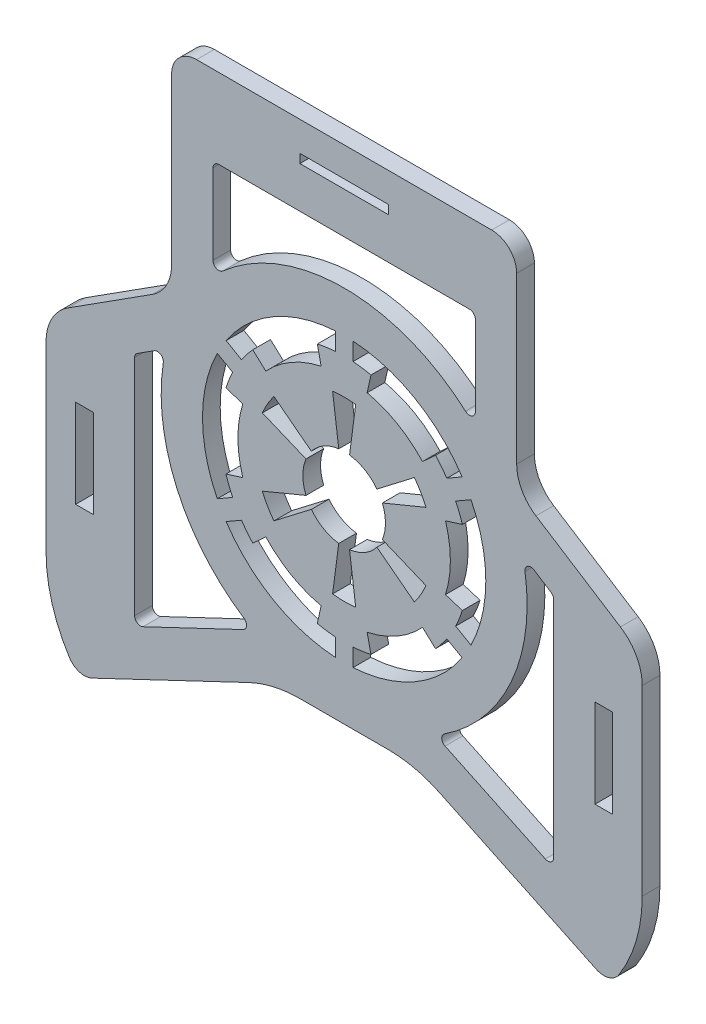
SolidWorks part; units mm, degrees
ref_plane "Front Plane" through (0, 0, 0) normal (0, 0, 1) x (1, 0, 0)
ref_plane "Top Plane" through (0, 0, 0) normal (0, 1, 0) x (1, 0, 0)
ref_plane "Right Plane" through (0, 0, 0) normal (1, 0, 0) x (0, 0, -1)
sketch "Sketch2" plane through (0, 0, 0) normal (0, 0, 1) x (1, 0, 0)
  line L4 (93, 2.1) -> (93, 62.1)
  line L5 (68, 87.1) -> (17, 87.1)
  line L6 (-8, 62.1) -> (-8, 2.1)
  line L7 (17, -22.9) -> (68, -22.9)
  line L8 (93, 2.1) -> (93, 62.1)
  line L9 (68, 87.1) -> (17, 87.1)
  line L10 (-8, 62.1) -> (-8, 2.1)
  line L11 (17, -22.9) -> (68, -22.9)
  line L13 (-3, 26.6) -> (-3, 11.6)
  line L14 (0, 26.6) -> (-3, 26.6)
  line L15 (0, 11.6) -> (0, 26.6)
  line L16 (-3, 11.6) -> (0, 11.6)
  line L17 (-3, 26.6) -> (-3, 11.6)
  line L18 (0, 26.6) -> (-3, 26.6)
  line L19 (0, 11.6) -> (0, 26.6)
  line L20 (-3, 11.6) -> (0, 11.6)
  line L22 (85, 26.6) -> (85, 11.6)
  line L23 (88, 26.6) -> (85, 26.6)
  line L24 (88, 11.6) -> (88, 26.6)
  line L25 (85, 11.6) -> (88, 11.6)
  line L26 (85, 26.6) -> (85, 11.6)
  line L27 (88, 26.6) -> (85, 26.6)
  line L28 (88, 11.6) -> (88, 26.6)
  line L29 (85, 11.6) -> (88, 11.6)
  line L31 (35, 82.1) -> (35, 80.6)
  line L32 (50, 82.1) -> (35, 82.1)
  line L33 (50, 80.6) -> (50, 82.1)
  line L34 (35, 80.6) -> (50, 80.6)
  line L35 (35, 82.1) -> (35, 80.6)
  line L36 (50, 82.1) -> (35, 82.1)
  line L37 (50, 80.6) -> (50, 82.1)
  line L38 (35, 80.6) -> (50, 80.6)
  arc A4 (93, 62.1) -> (68, 87.1) centre (68, 62.1) ccw
  arc A5 (17, 87.1) -> (-8, 62.1) centre (17, 62.1) ccw
  arc A6 (-8, 2.1) -> (17, -22.9) centre (17, 2.1) ccw
  arc A7 (68, -22.9) -> (93, 2.1) centre (68, 2.1) ccw
  arc A8 (93, 62.1) -> (68, 87.1) centre (68, 62.1) ccw
  arc A9 (17, 87.1) -> (-8, 62.1) centre (17, 62.1) ccw
  arc A10 (-8, 2.1) -> (17, -22.9) centre (17, 2.1) ccw
  arc A11 (68, -22.9) -> (93, 2.1) centre (68, 2.1) ccw
  dimension "D1" = 0
  dimension "D2" = 0
  dimension "D3" = 0
  dimension "D4" = 0
extrude "Boss-Extrude1" add sketch "Sketch2" along normal blind 3
sketch "Sketch3" plane through (0, 0, 3) normal (0, 0, 1) x (1, 0, 0)
  line L0 (68, 87.1) -> (17, 87.1) construction
  line L1 (13.2678, 82.8678) -> (13.2678, 54.8678)
  line L2 (10, 48.9032) -> (-8, 37.4065)
  line L3 (-8, 62.1) -> (-8, 2.1) construction
  line L4 (-2.4738, -13.577) -> (30.5, 2.1)
  line L5 (30.5, 2.1) -> (54.5, 2.1)
  line L6 (42.5, 87.1) -> (42.5, -22.9) construction
  line L7 (17, -22.9) -> (68, -22.9) construction
  line L8 (17.5, 87.1) -> (67.5, 87.1)
  line L9 (-8, 37.4065) -> (-8, 106.023)
  line L10 (-8, 106.023) -> (93, 106.023)
  line L11 (-2.4738, -13.577) -> (-2.4738, -35.5328)
  line L12 (-2.4738, -35.5328) -> (87.4738, -35.5328)
  line L13 (87.4738, -13.577) -> (87.4738, -35.5328)
  line L14 (93, 37.4065) -> (93, 106.023)
  line L15 (87.4738, -13.577) -> (54.5, 2.1)
  line L16 (75, 48.9032) -> (93, 37.4065)
  line L17 (71.7322, 82.8678) -> (71.7322, 54.8678)
  arc A0 (17.5, 87.1) -> (13.2678, 82.8678) centre (17.5, 82.8678) ccw
  arc A1 (13.2678, 54.8678) -> (10, 48.9032) centre (6.1904, 54.8678) cw
  arc A2 (-8, 2.1) -> (17, -22.9) centre (17, 2.1) ccw construction
  arc A3 (71.7322, 54.8678) -> (75, 48.9032) centre (78.8096, 54.8678) ccw
  arc A4 (67.5, 87.1) -> (71.7322, 82.8678) centre (67.5, 82.8678) cw
  point P29 (42.5, 2.1)
  point P30 (42.5, 106.023)
  point P31 (42.5, -35.5328)
  dimension "D1" = 12
  dimension "D2" = 25
  dimension "D3" = 25
  dimension "D4" = 28
  dimension "D6" = 18
extrude "Cut-Extrude1" cut sketch "Sketch3" against normal through all
fillet "Fillet1" radius 3 2 edges at (-2.4738, -13.577, 1.5) (87.4738, -13.577, 1.5)
fillet "Fillet2" radius 20 2 edges at (30.5, 2.1, 1.5) (54.5, 2.1, 1.5)
fillet "Fillet3" radius 8 2 edges at (-8, 37.4065, 1.5) (93, 37.4065, 1.5)
sketch "Sketch5" plane through (0, 0, 3) normal (0, 0, 1) x (1, 0, 0)
  line L0 (42.5, 87.1) -> (42.5, 2.1) construction
  line L1 (67.5, 87.1) -> (17.5, 87.1) construction
  line L2 (49.9876, 2.1) -> (35.0124, 2.1) construction
  line L3 (149.0087, 53.9587) -> (120.8587, 53.9587) construction
  line L4 (146.9102, 53.2087) -> (145.4069, 53.2087)
  line L5 (146.9102, 54.7087) -> (145.4069, 54.7087)
  line L6 (146.9102, 54.7087) -> (146.1585, 53.9587) construction
  line L7 (146.1585, 53.9587) -> (145.4069, 53.2087) construction
  line L8 (134.9337, 53.9587) -> (145.1848, 56.2313) construction
  line L9 (134.9337, 53.9587) -> (145.1848, 51.6861) construction
  line L10 (145.1848, 51.6861) -> (145.1848, 53.9587) construction
  line L11 (145.1848, 53.9587) -> (145.1848, 56.2313) construction
  line L12 (145.1848, 56.2313) -> (143.7203, 55.9066)
  line L13 (145.1848, 51.6861) -> (143.7203, 52.0107)
  line L14 (140.2724, 43.2117) -> (139.5208, 44.5137)
  line L15 (138.0911, 43.9447) -> (137.64, 45.3752)
  line L16 (142.0274, 46.2173) -> (141.014, 47.3232)
  line L17 (141.5715, 43.9617) -> (140.8198, 45.2637)
  line L18 (128.2959, 43.9617) -> (129.0476, 45.2637)
  line L19 (127.84, 46.2173) -> (128.8534, 47.3232)
  line L20 (131.7763, 43.9447) -> (132.2273, 45.3752)
  line L21 (129.5949, 43.2117) -> (130.3466, 44.5137)
  line L22 (122.9571, 54.7087) -> (124.4605, 54.7087)
  line L23 (124.6826, 56.2313) -> (126.147, 55.9066)
  line L24 (124.6826, 51.6861) -> (126.147, 52.0107)
  line L25 (122.9571, 53.2087) -> (124.4605, 53.2087)
  line L26 (129.5949, 64.7057) -> (130.3466, 63.4037)
  line L27 (131.7763, 63.9727) -> (132.2273, 62.5421)
  line L28 (127.84, 61.7001) -> (128.8534, 60.5942)
  line L29 (128.2959, 63.9557) -> (129.0476, 62.6537)
  line L30 (141.5715, 63.9557) -> (140.8198, 62.6537)
  line L31 (142.0274, 61.7001) -> (141.014, 60.5942)
  line L32 (138.0911, 63.9727) -> (137.64, 62.5421)
  line L33 (140.2724, 64.7057) -> (139.5208, 63.4037)
  line L34 (134.9337, 53.9587) -> (142.3695, 54.9376) construction
  line L35 (134.9337, 53.9587) -> (142.3695, 52.9797) construction
  line L36 (142.3695, 52.9797) -> (142.3695, 53.9587) construction
  line L37 (142.3695, 53.9587) -> (142.3695, 54.9376) construction
  line L38 (142.3695, 54.9376) -> (138.4037, 54.4155)
  line L39 (142.3695, 52.9797) -> (138.4037, 53.5019)
  line L40 (139.4994, 48.0085) -> (137.0643, 51.182)
  line L41 (137.8038, 47.0296) -> (136.2731, 50.7251)
  line L42 (132.0636, 47.0296) -> (133.5943, 50.7251)
  line L43 (130.368, 48.0085) -> (132.803, 51.182)
  line L44 (127.4978, 52.9797) -> (131.4636, 53.5019)
  line L45 (127.4978, 54.9376) -> (131.4636, 54.4155)
  line L46 (130.368, 59.9088) -> (132.803, 56.7354)
  line L47 (132.0636, 60.8878) -> (133.5943, 57.1923)
  line L48 (137.8038, 60.8878) -> (136.2731, 57.1923)
  line L49 (139.4994, 59.9088) -> (137.0643, 56.7354)
  line L50 (41, 59.0531) -> (41, 56.0464)
  line L51 (41, 56.0464) -> (42.5, 57.5497) construction
  line L52 (44, 59.0531) -> (44, 56.0464)
  line L53 (42.5, 57.5497) -> (44, 59.0531) construction
  line L54 (42.5, 35.1) -> (47.0452, 55.6022) construction
  line L55 (47.0452, 55.6022) -> (42.5, 55.6022) construction
  line L56 (42.5, 55.6022) -> (37.9548, 55.6022) construction
  line L57 (37.9548, 55.6022) -> (42.5, 35.1) construction
  line L58 (37.9548, 55.6022) -> (38.6041, 52.6733)
  line L59 (47.0452, 55.6022) -> (46.3959, 52.6733)
  line L60 (42.5, 35.1) -> (44.4579, 49.9717) construction
  line L61 (44.4579, 49.9717) -> (42.5, 49.9717) construction
  line L62 (42.5, 49.9717) -> (40.5421, 49.9717) construction
  line L63 (40.5421, 49.9717) -> (42.5, 35.1) construction
  line L64 (44.4579, 49.9717) -> (43.4137, 42.0401)
  line L65 (40.5421, 49.9717) -> (41.5863, 42.0401)
  line L66 (63.994, 45.7775) -> (61.3901, 44.2741)
  line L67 (62.494, 48.3756) -> (59.8901, 46.8722)
  line L68 (62.5281, 41.4148) -> (59.6669, 40.5127)
  line L69 (57.9828, 49.2874) -> (55.771, 47.2606)
  line L70 (54.4003, 44.2314) -> (48.0535, 39.3613)
  line L71 (56.3582, 40.8403) -> (48.9672, 37.7788)
  line L72 (62.494, 21.8244) -> (59.8901, 23.3278)
  line L73 (63.994, 24.4225) -> (61.3901, 25.9259)
  line L74 (57.9828, 20.9126) -> (55.771, 22.9394)
  line L75 (62.5281, 28.7852) -> (59.6669, 29.6873)
  line L76 (56.3582, 29.3597) -> (48.9672, 32.4212)
  line L77 (54.4003, 25.9686) -> (48.0535, 30.8387)
  line L78 (41, 11.1469) -> (41, 14.1536)
  line L79 (44, 11.1469) -> (44, 14.1536)
  line L80 (37.9548, 14.5978) -> (38.6041, 17.5267)
  line L81 (47.0452, 14.5978) -> (46.3959, 17.5267)
  line L82 (44.4579, 20.2283) -> (43.4137, 28.1599)
  line L83 (40.5421, 20.2283) -> (41.5863, 28.1599)
  line L84 (21.006, 24.4225) -> (23.6099, 25.9259)
  line L85 (22.506, 21.8244) -> (25.1099, 23.3278)
  line L86 (22.4719, 28.7852) -> (25.3331, 29.6873)
  line L87 (27.0172, 20.9126) -> (29.229, 22.9394)
  line L88 (30.5997, 25.9686) -> (36.9465, 30.8387)
  line L89 (28.6418, 29.3597) -> (36.0328, 32.4212)
  line L90 (22.506, 48.3756) -> (25.1099, 46.8722)
  line L91 (21.006, 45.7775) -> (23.6099, 44.2741)
  line L92 (27.0172, 49.2874) -> (29.229, 47.2606)
  line L93 (22.4719, 41.4148) -> (25.3331, 40.5127)
  line L94 (28.6418, 40.8403) -> (36.0328, 37.7788)
  line L95 (30.5997, 44.2314) -> (36.9465, 39.3613)
  circle A0 centre (134.9337, 53.9587) radius 12
  circle A1 centre (134.9337, 53.9587) radius 10.5
  circle A2 centre (134.9337, 53.9587) radius 9
  circle A3 centre (134.9337, 53.9587) radius 7.5
  circle A4 centre (134.9337, 53.9587) radius 3.5
  circle A5 centre (42.5, 35.1) radius 24
  circle A6 centre (42.5, 35.1) radius 21
  circle A7 centre (42.5, 35.1) radius 18
  circle A8 centre (42.5, 35.1) radius 15
  circle A9 centre (42.5, 35.1) radius 7
  point P65 (134.9337, 53.9587)
  point P90 (134.9337, 53.9587)
  point P175 (42.5, 35.1)
  dimension "D8" = 48
  dimension "D2" = 42
  dimension "D5" = 36
  dimension "D9" = 30
  dimension "D10" = 14
  dimension "D1" = 52
  dimension "D3" = 1.5
  dimension "D4" = 25
  dimension "D6" = 11
  dimension "D7" = 15
  dimension "D11" = 3
  dimension "D12" = 25
  dimension "D13" = 15
  dimension "D14" = 6
extrude "Cut-Extrude2" cut sketch "Sketch5" against normal through all contours A6 L50 A5 L90 | A6 L91 A5 L84 | A6 L85 A5 L78 | A6 L79 A5 L72 | A6 L73 A5 L66 | A6 L67 A5 L52 | A7 L58 A6 L92 | A7 L93 A6 L86 | A7 L87 A6 L80 | A7 L81 A6 L74 | A7 L75 A6 L68 | A7 L69 A6 L59 | A9 L95 A8 L94 | A9 L89 A8 L88 | A9 L71 A8 L70 | A9 L77 A8 L76 | A9 L83 A8 L82 | A9 L64 A8 L65 | A9
sketch "Sketch6" plane through (0, 0, 3) normal (0, 0, 1) x (1, 0, 0)
  line L0 (20.2678, 73.6) -> (20.2678, 56.7039)
  line L1 (64.7322, 73.6) -> (20.2678, 73.6)
  line L2 (7, 38.6811) -> (7, -1.3219)
  line L3 (13.2678, 54.8678) -> (13.2678, 82.8678) construction
  line L4 (7, -1.3219) -> (27.0631, 8.2169)
  line L5 (7, 38.6811) -> (12.2916, 42.0609)
  line L6 (26.4248, 0.1625) -> (-0.2186, -12.5048) construction
  line L7 (64.7322, 73.6) -> (64.7322, 56.7039)
  line L8 (0, 11.6) -> (0, 26.6) construction
  line L9 (42.5, 87.1) -> (42.5, 2.1) construction
  line L10 (67.5, 87.1) -> (17.5, 87.1) construction
  line L11 (49.9876, 2.1) -> (35.0124, 2.1) construction
  line L12 (64.7322, 73.6) -> (42.5, 73.6) construction
  line L13 (42.5, 73.6) -> (64.7322, 73.6) construction
  line L14 (35, 80.6) -> (50, 80.6) construction
  line L15 (71.7322, 82.8678) -> (71.7322, 54.8678) construction
  line L16 (-4.3062, 39.7657) -> (10, 48.9032) construction
  line L17 (78, 38.6811) -> (72.7084, 42.0609)
  line L18 (78, -1.3219) -> (57.9369, 8.2169)
  line L19 (78, 38.6811) -> (78, -1.3219)
  arc A2 (16.6744, 17.9524) -> (40.5625, 4.1606) centre (42.5, 35.1) ccw
  arc A3 (16.7909, 17.7783) -> (27.0631, 8.2169) centre (42.5, 35.1) ccw
  arc A4 (68.2091, 17.7783) -> (57.9369, 8.2169) centre (42.5, 35.1) cw
  arc A5 (14.7369, 48.8918) -> (14.7369, 21.3082) centre (42.5, 35.1) ccw
  arc A6 (12.2916, 42.0609) -> (16.7909, 17.7783) centre (42.5, 35.1) ccw
  arc A7 (72.7084, 42.0609) -> (68.2091, 17.7783) centre (42.5, 35.1) cw
  arc A13 (40.5625, 66.0394) -> (16.6744, 52.2476) centre (42.5, 35.1) ccw
  arc A14 (42.5, 66.1) -> (20.2678, 56.7039) centre (42.5, 35.1) ccw
  arc A16 (68.3256, 52.2476) -> (44.4375, 66.0394) centre (42.5, 35.1) ccw
  arc A17 (64.7322, 56.7039) -> (42.5, 66.1) centre (42.5, 35.1) ccw
  dimension "D1" = 7
  dimension "D3" = 7
  dimension "D4" = 7
  dimension "D5" = 7
  dimension "D6" = 7
  dimension "D8" = 7
  dimension "D9" = 7
  dimension "D10" = 7
  dimension "D2" = 7
  dimension "D7" = 7
extrude "Cut-Extrude3" cut sketch "Sketch6" against normal through all
fillet "Fillet4" radius 1 12 edges at (78, 38.6811, 1.5) (72.7084, 42.0609, 1.5) (57.9369, 8.2169, 1.5) (78, -1.3219, 1.5) (7, -1.3219, 1.5) (27.0631, 8.2169, 1.5) (7, 38.6811, 1.5) (12.2916, 42.0609, 1.5) (20.2678, 56.7039, 1.5) (64.7322, 56.7039, 1.5) (64.7322, 73.6, 1.5) (20.2678, 73.6, 1.5)
